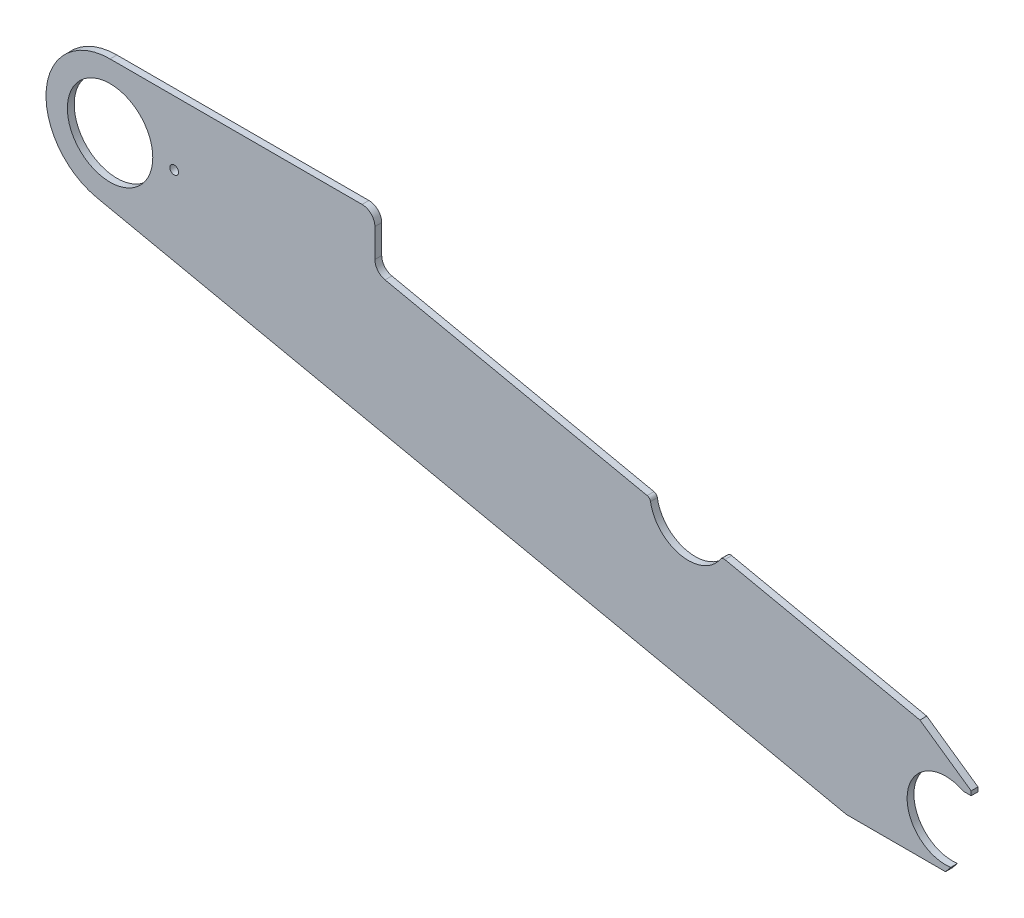
SolidWorks part; units mm, degrees
material "Q355"
ref_plane "前视基准面" through (0, 0, 0) normal (0, 0, 1) x (1, 0, 0)
ref_plane "上视基准面" through (0, 0, 0) normal (0, 1, 0) x (1, 0, 0)
ref_plane "右视基准面" through (0, 0, 0) normal (1, 0, 0) x (0, 0, -1)
sketch "草图1" plane through (0, 0, 0) normal (0, 0, 1) x (1, 0, 0)
  line L0 (0, 0) -> (978, -208) construction
  line L1 (0, 75) -> (310, 75)
  line L2 (310, 75) -> (310, 14.478)
  line L3 (310, 14.478) -> (632.182, -54.0433)
  line L4 (948, -121.2111) -> (1008, -163)
  line L5 (978, -260) -> (861.9685, -260)
  line L6 (-15.602, -73.3592) -> (861.9685, -260)
  line L7 (716.2936, -71.9321) -> (948, -121.2111)
  line L8 (978, -260) -> (984, -252.5982)
  line L10 (1008, -163) -> (1008, -168)
  line L11 (1008, -168) -> (998.6155, -168)
  circle A0 centre (0, 0) radius 50
  arc A1 (632.182, -54.0433) -> (716.2936, -71.9321) centre (677, -50) ccw
  arc A2 (998.6155, -168) -> (984, -252.5982) centre (978, -208) ccw
  arc A3 (0, 75) -> (-15.602, -73.3592) centre (0, 0) ccw
  dimension "D2" = 90
  dimension "D3" = 45
  dimension "D8" = 75
  dimension "D11" = 30
  dimension "D4" = 100
  dimension "D6" = 310
  dimension "D12" = 978
  dimension "D16" = 208
  dimension "D18" = 41.7889
  dimension "D5" = 158
  dimension "D7" = 301
  dimension "D9" = 335
  dimension "D10" = 6
  dimension "D13" = 40
  dimension "D14" = 5
  dimension "D15" = 60
extrude "凸台-拉伸1" add sketch "草图1" along normal blind 8
fillet "圆角1" radius 15 2 edges at (310, 14.478, 4) (310, 75, 4)
hole_wizard "M12 螺纹孔1" positions "草图2" profile "草图3" tap size "M12" standard "GB" end condition through all
sketch "草图2" plane through (0, 0, 8) normal (0, 0, 1) x (1, 0, 0)
  point P0 (75, 0)
  dimension "D1" = 75
sketch "草图3" plane through (75, 0, 8) normal (1, 0, 0) x (0, -1, 0)
  line L0 (0, 0) -> (0, 8)
  line L1 (0, 8) -> (5.1, 8)
  line L2 (5.1, 8) -> (5.1, 0)
  line L5 (5.1, 0) -> (0, 0)
  line L11 (0, -6.35) -> (0, 107.95) construction
  dimension "通孔螺纹孔钻头直径" = 10.2
  dimension "通孔螺纹孔钻头深度" = 8
cosmetic thread "孔螺蚊线1" parameters "D2"=12
fillet "圆角2" radius 5 2 edges at (716.2936, -71.9321, 4) (632.182, -54.0433, 4)
